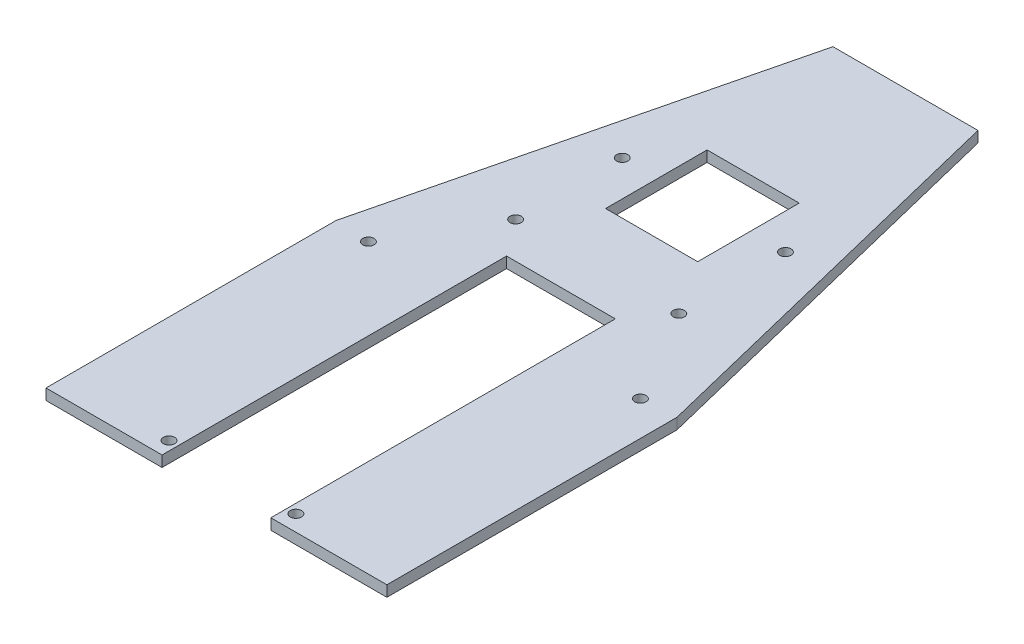
SolidWorks part; units mm, degrees
material "Acrylic (Medium-high impact)"
ref_plane "Front Plane" through (0, 0, 0) normal (0, 0, 1) x (1, 0, 0)
ref_plane "Top Plane" through (0, 0, 0) normal (0, 1, 0) x (1, 0, 0)
ref_plane "Right Plane" through (0, 0, 0) normal (1, 0, 0) x (0, 0, -1)
sketch "Sketch3" plane through (0, 0, 0) normal (0, 1, 0) x (1, 0, 0)
  line L0 (-15, -95) -> (-47, -95)
  line L1 (-47, -95) -> (-47, -15)
  line L2 (-47, -15) -> (-20, 95)
  line L3 (-20, 95) -> (20, 95)
  line L4 (20, 95) -> (47, -15)
  line L5 (47, -15) -> (47, -95)
  line L6 (47, -95) -> (15, -95)
  line L7 (15, -95) -> (15, 0)
  line L8 (15, 0) -> (-15, 0)
  line L9 (-15, 0) -> (-15, -95)
  point P11 (0, 0)
  dimension "D1" = 30
  dimension "D2" = 32
  dimension "D3" = 95
  dimension "D4" = 80
  dimension "D5" = 110
  dimension "D6" = 40
extrude "Body" add sketch "Sketch3" along normal blind 3
sketch "Sketch5" plane through (0, 3, 0) normal (0, 1, 0) x (1, 0, 0)
  line L0 (0, 0) -> (0, 25) construction
  line L1 (-12.7, 25) -> (12.7, 25)
  line L2 (-12.7, 25) -> (-12.7, 53)
  line L3 (-12.7, 53) -> (12.7, 53)
  line L4 (12.7, 25) -> (12.7, 53)
  line L5 (-15, 0) -> (15, 0) construction
  line L7 (0, 53) -> (0, 25) construction
  dimension "D1" = 25.4
  dimension "D2" = 28
  dimension "D3" = 25
extrude "Protoboard Mount" cut sketch "Sketch5" against normal blind 10
sketch "Sketch8" plane through (0, 3, 0) normal (0, 1, 0) x (1, 0, 0)
  line L0 (-22.5, 39.4) -> (22.5, 39.4) construction
  line L1 (-37.5, -15.6) -> (37.5, -15.6) construction
  line L2 (-17.5, -90.6) -> (17.5, -90.6) construction
  line L3 (0, 39.4) -> (0, -90.6) construction
  line L4 (-47, -95) -> (-15, -95) construction
  circle A0 centre (-22.5, 39.4) radius 1.55
  circle A1 centre (22.5, 39.4) radius 1.55
  circle A2 centre (37.5, -15.6) radius 1.55
  circle A3 centre (-37.5, -15.6) radius 1.55
  circle A4 centre (-17.5, -90.6) radius 1.55
  circle A5 centre (17.5, -90.6) radius 1.55
  point P14 (0, -15.6)
  dimension "D1" = 3.1
  dimension "D2" = 45
  dimension "D3" = 75
  dimension "D4" = 35
  dimension "D5" = 75
  dimension "D6" = 55
  dimension "D7" = 4.4
extrude "Stand Off Mount" cut sketch "Sketch8" against normal blind 10
sketch "Sketch9" plane through (0, 3, 0) normal (0, 1, 0) x (1, 0, 0)
  line L0 (-22.5, 10) -> (22.5, 10) construction
  line L1 (0, 10) -> (0, 0) construction
  circle A0 centre (-22.5, 10) radius 1.55
  circle A1 centre (22.5, 10) radius 1.55
  dimension "D2" = 3.1
  dimension "D1" = 45
  dimension "D3" = 10
extrude "Phone Mount" cut sketch "Sketch9" against normal blind 10
